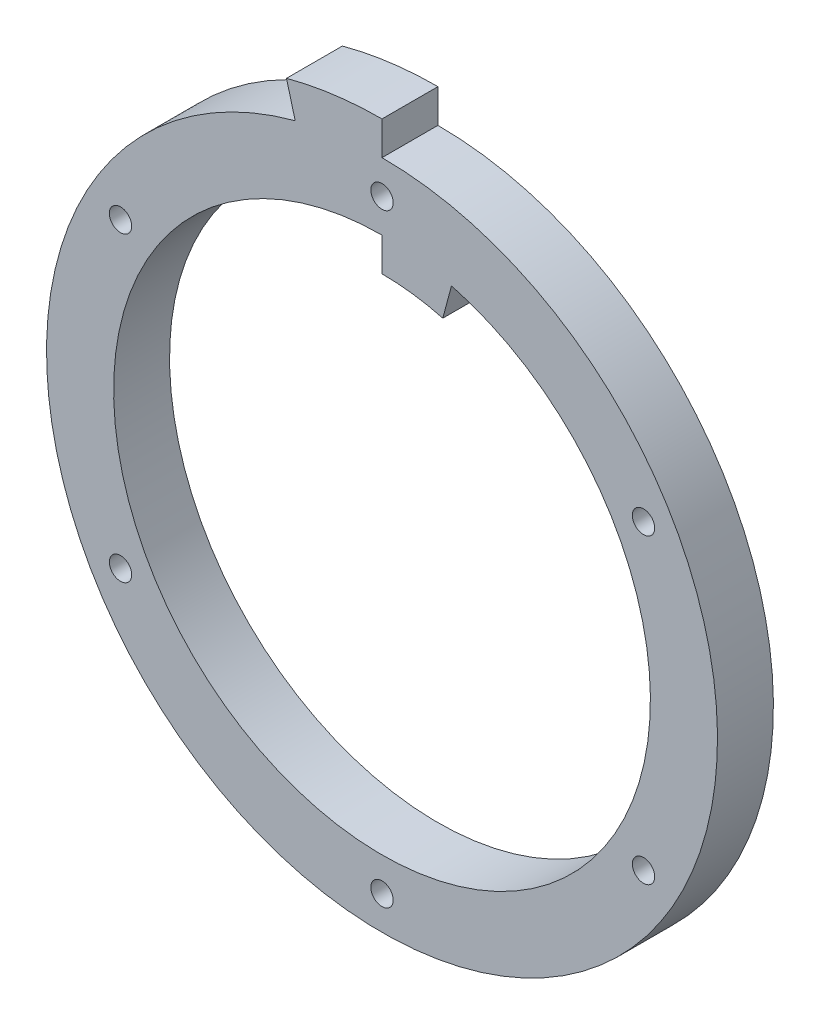
SolidWorks part; units mm, degrees
ref_plane "前视基准面" through (0, 0, 0) normal (0, 0, 1) x (1, 0, 0)
ref_plane "上视基准面" through (0, 0, 0) normal (0, 1, 0) x (1, 0, 0)
ref_plane "右视基准面" through (0, 0, 0) normal (1, 0, 0) x (0, 0, -1)
sketch "草图1" plane through (0, 0, 0) normal (0, 0, 1) x (1, 0, 0)
  circle A0 centre (0, 0) radius 24
  circle A1 centre (0, 0) radius 30
  dimension "D1" = 48
  dimension "D2" = 60
extrude "凸台-拉伸1" add sketch "草图1" along normal blind 5
sketch "草图2" plane through (0, 0, 5) normal (0, 0, 1) x (1, 0, 0)
  line L0 (0, 0) -> (0, 27) construction
  circle A0 centre (0, 27) radius 1
  circle A1 centre (23.3827, 13.5) radius 1
  circle A2 centre (23.3827, -13.5) radius 1
  circle A3 centre (0, -27) radius 1
  circle A4 centre (-23.3827, -13.5) radius 1
  circle A5 centre (-23.3827, 13.5) radius 1
  point P16 (0, 0)
  dimension "D2" = 2
  dimension "D1" = 27
  dimension "D3" = 6
extrude "切除-拉伸1" cut sketch "草图2" against normal through all
sketch "草图3" plane through (0, 0, 5) normal (0, 0, 1) x (1, 0, 0)
  line L0 (0, 30) -> (0, 0) construction
  line L1 (0, 0) -> (7.7646, 28.9778) construction
  line L2 (5.4352, 20.2844) -> (6.2117, 23.1822)
  line L3 (0, 24) -> (0, 21)
  line L4 (0, 30) -> (0, 33)
  line L5 (-8.541, 31.8756) -> (0, 0) construction
  line L6 (-7.7646, 28.9778) -> (-8.541, 31.8756)
  circle A0 centre (0, 0) radius 30 construction
  arc A1 (5.4352, 20.2844) -> (0, 21) centre (0, 0) ccw
  circle A2 centre (0, 0) radius 24 construction
  arc A3 (6.2117, 23.1822) -> (0, 24) centre (0, 0) ccw
  arc A4 (0, 33) -> (-8.541, 31.8756) centre (0, 0) ccw
  arc A5 (0, 30) -> (-7.7646, 28.9778) centre (0, 0) ccw
  dimension "D2" = 42
  dimension "D3" = 66
  dimension "D1" = 15
  dimension "D4" = 15
extrude "凸台-拉伸2" add sketch "草图3" against normal blind 5
